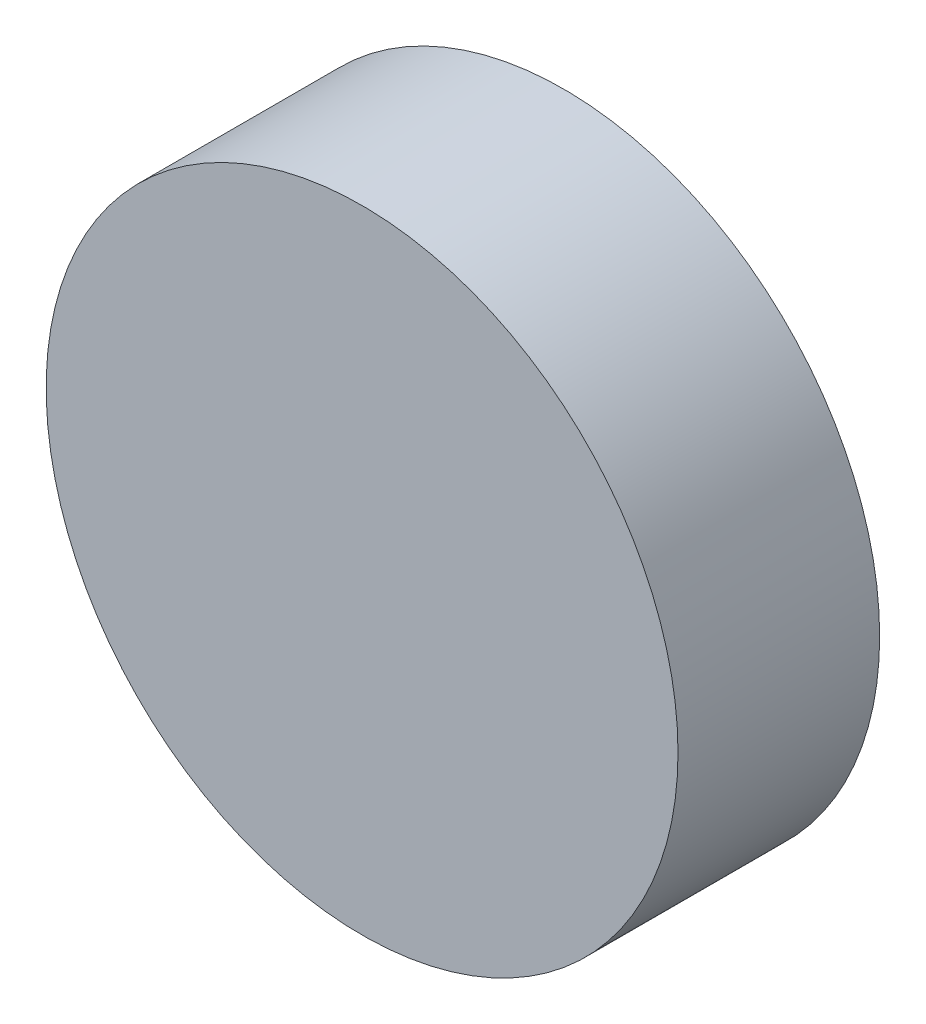
SolidWorks part; units mm, degrees
ref_plane "Front Plane" through (0, 0, 0) normal (0, 0, 1) x (1, 0, 0)
ref_plane "Top Plane" through (0, 0, 0) normal (0, 1, 0) x (1, 0, 0)
ref_plane "Right Plane" through (0, 0, 0) normal (1, 0, 0) x (0, 0, -1)
sketch "Sketch1" plane through (0, 0, 0) normal (0, 0, 1) x (1, 0, 0)
  circle A0 centre (0, 0) radius 45
  circle A1 centre (0, 0) radius 47
  circle A2 centre (0, 0) radius 42.6
  dimension "D1" = 90
  dimension "D2" = 94
  dimension "D3" = 2.4
extrude "Boss-Extrude1" add sketch "Sketch1" along normal mid plane 30 contours A1
sketch "Sketch2" plane through (0, 0, 0) normal (0, 0, 1) x (1, 0, 0)
  line L0 (0, 0) -> (0, 47) construction
  line L1 (-8.3772, 44.2134) -> (8.3772, 44.2134) construction
  line L2 (0, 0) -> (-7.7444, 41.8901) construction
  line L3 (0, 21.1971) -> (-9.7619, 48.0178) construction
  line L4 (3.2786, 46.8855) -> (0, 0) construction
  circle A0 centre (0, 0) radius 47 construction
  arc A1 (-10.3572, 47.8929) -> (-7.7444, 41.8901) centre (-22.0025, 39.2542) cw
  arc A2 (10.3572, 47.8929) -> (7.7444, 41.8901) centre (22.0025, 39.2542) ccw
  circle A3 centre (0, 0) radius 42.6 construction
  arc A4 (7.7444, 41.8901) -> (-7.7444, 41.8901) centre (0, 0) ccw
  circle A5 centre (0, 0) radius 47 construction
  circle A6 centre (0, 0) radius 45 construction
  circle A7 centre (0, 0) radius 49
  arc A8 (10.3572, 47.8929) -> (-10.3572, 47.8929) centre (0, 0) ccw
  dimension "D2" = 20
  dimension "D3" = 4
  dimension "D4" = 44.0049
  dimension "D1" = 2
equation "\"Mofule\"= 2mm"
equation "\"No of teeth\"= 45"
equation "\"D1@Sketch1\"=\"Mofule\"*\"No of teeth\""
equation "\"D2@Sketch1\"=\"Mofule\"*(\"No of teeth\"+2)"
equation "\"D3@Sketch2\"= 180 /\"No of teeth\""
